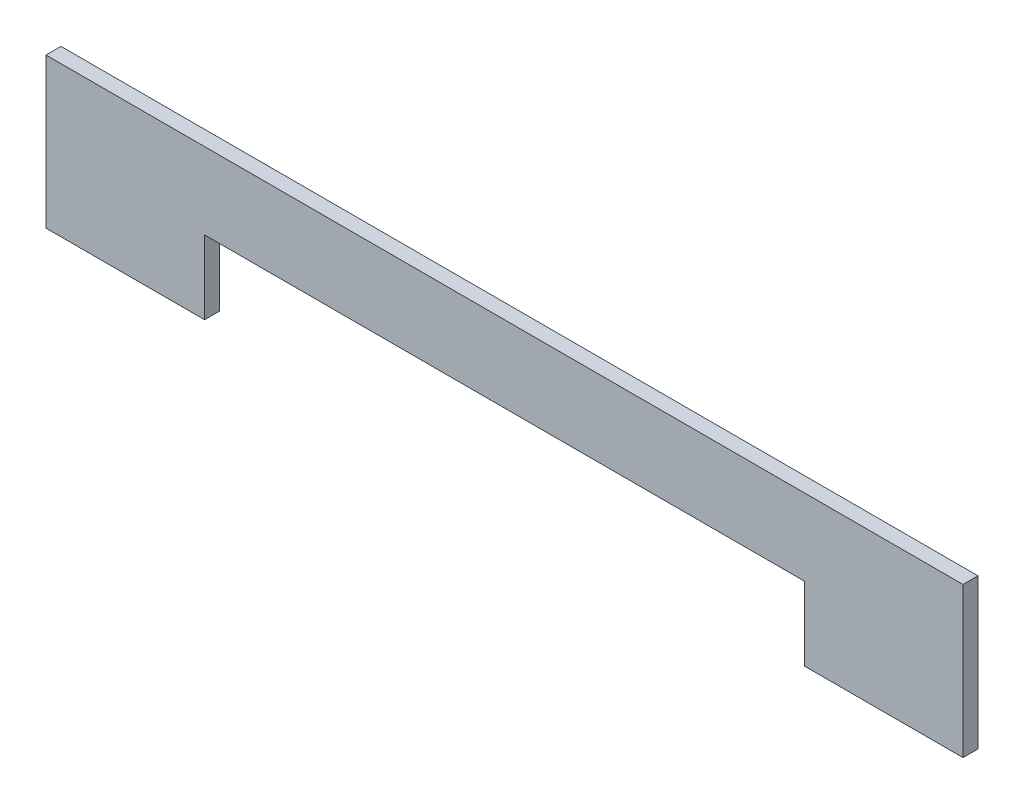
SolidWorks part; units mm, degrees
material "Простая углеродистая сталь"
ref_plane "Спереди" through (0, 0, 0) normal (0, 0, 1) x (1, 0, 0)
ref_plane "Сверху" through (0, 0, 0) normal (0, 1, 0) x (1, 0, 0)
ref_plane "Справа" through (0, 0, 0) normal (1, 0, 0) x (0, 0, -1)
sketch "Эскиз1" plane through (0, 0, 0) normal (0, 0, 1) x (1, 0, 0)
  line L1 (0, 0) -> (6115, 0)
  line L2 (0, 0) -> (0, -1000)
  line L3 (0, -1000) -> (6115, -1000)
  line L4 (6115, 0) -> (6115, -1000)
  line L5 (3057.5, -1000) -> (3057.5, 0) construction
  line L6 (0, -500) -> (6115, -500) construction
  point P88 (3057.5, -500)
  dimension "D1" = 6115
  dimension "D2" = 1000
extrude "Бобышка-Вытянуть1" add sketch "Эскиз1" along normal blind 100
sketch "Эскиз2" plane through (0, 0, 0) normal (0, 0, -1) x (-1, 0, 0)
  line L0 (-3057.5, -1000) -> (-3057.5, 0) construction
  line L1 (0, -1000) -> (-6115, -1000) construction
  line L2 (-6115, 0) -> (0, 0) construction
  line L4 (-5057.5, -510) -> (-1057.5, -510)
  line L5 (-5057.5, -510) -> (-5057.5, -1000)
  line L6 (-5057.5, -1000) -> (-1057.5, -1000)
  line L7 (-1057.5, -510) -> (-1057.5, -1000)
  line L8 (-3057.5, -1000) -> (-3057.5, -510) construction
  line L9 (-5057.5, -755) -> (-1057.5, -755) construction
  point P10 (-1082.7616, -1000)
  point P11 (-1065.1569, -1000)
  point P12 (-5031.4092, -1000)
  point P602 (-3057.5, -755)
  dimension "D1" = 4000
  dimension "D2" = 490
extrude "Вырез-Вытянуть1" cut sketch "Эскиз2" against normal through all
